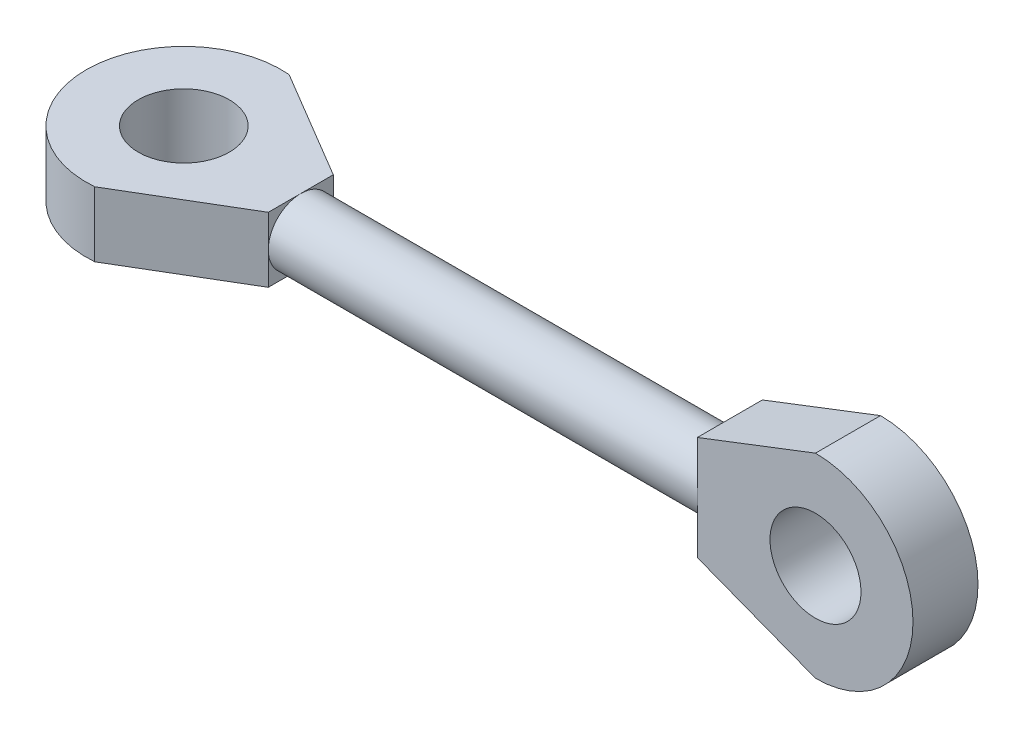
SolidWorks part; units mm, degrees
ref_plane "Ön Düzlem" through (0, 0, 0) normal (0, 0, 1) x (1, 0, 0)
ref_plane "Üst Düzlem" through (0, 0, 0) normal (0, 1, 0) x (1, 0, 0)
ref_plane "Sağ Düzlem" through (0, 0, 0) normal (1, 0, 0) x (0, 0, -1)
sketch "Sketch1" plane through (0, 0, 0) normal (0, 0, 1) x (1, 0, 0)
  line L2 (0, 7.5) -> (-9.0884, 4)
  line L3 (0, -7.5) -> (-9.0884, -4)
  line L4 (-9.0884, 4) -> (-9.0884, -4)
  line L5 (-42.3116, 4) -> (-9.0884, 4)
  line L6 (-51.4, -7.5) -> (-42.3116, -4)
  line L7 (-42.3116, 4) -> (-42.3116, -4)
  line L8 (-51.4, 7.5) -> (-42.3116, 4)
  line L9 (-42.3116, -4) -> (-9.0884, -4)
  line L10 (10.2928, 0) -> (-63.5463, 0) construction
  circle A0 centre (0, 0) radius 3.5
  arc A1 (-51.4, 7.5) -> (-51.4, -7.5) centre (-51.4, 0) ccw
  arc A2 (0, -7.5) -> (0, 7.5) centre (0, 0) ccw
  circle A3 centre (-51.4, 0) radius 3.5
  dimension "D1" = 51.4
  dimension "D2" = 7
  dimension "D3" = 15
  dimension "D4" = 15
  dimension "D5" = 7
  dimension "D6" = 8
extrude "Boss-Extrude2" add sketch "Sketch1" along normal mid plane 5 contours L10 A2 L2 L4 A0 | A2 L10 A0 L4 L3
sketch "Sketch4" plane through (-9.0884, 0, 0) normal (-1, 0, 0) x (0, 0, 1)
  circle A0 centre (0, 0) radius 2.5
extrude "Boss-Extrude3" add sketch "Sketch4" along normal blind 33
sketch "Sketch8" plane through (0, 0, 0) normal (0, 1, 0) x (1, 0, 0)
  line L1 (-42.0884, 2.5) -> (-42.0884, -2.5)
  line L4 (-42.0884, 2.5) -> (-50.4627, 7.4739)
  line L5 (-42.0884, -2.5) -> (-50.4627, -7.4739)
  circle A0 centre (-51.0884, 0) radius 3.5
  arc A2 (-50.4627, 7.4739) -> (-50.4627, -7.4739) centre (-51.0884, 0) ccw
  point P8 (-42.0884, 0)
  dimension "D1" = 7
  dimension "D3" = 9
  dimension "D4" = 9.74
  dimension "D5" = 9.74
extrude "Boss-Extrude4" add sketch "Sketch8" along normal mid plane 5
